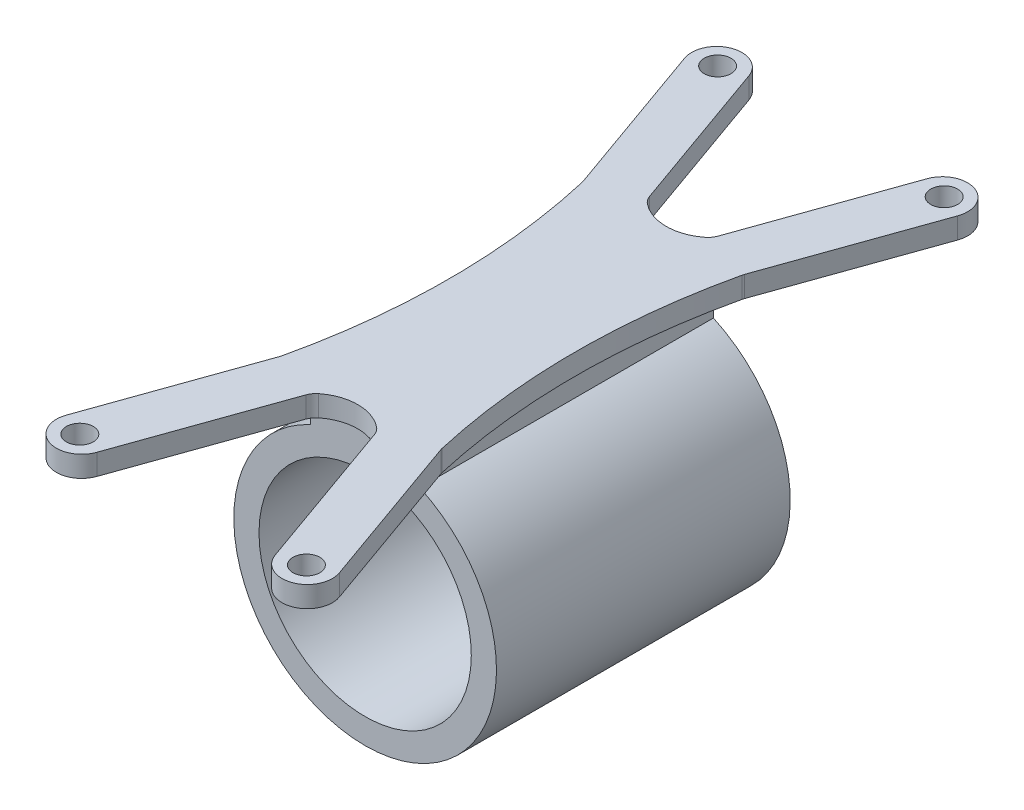
SolidWorks part; units mm, degrees
ref_plane "Front Plane" through (0, 0, 0) normal (0, 0, 1) x (1, 0, 0)
ref_plane "Top Plane" through (0, 0, 0) normal (0, 1, 0) x (1, 0, 0)
ref_plane "Right Plane" through (0, 0, 0) normal (1, 0, 0) x (0, 0, -1)
sketch "Sketch1" plane through (0, 0, 0) normal (0, 0, 1) x (1, 0, 0)
  circle A0 centre (0, 0) radius 12.65
  circle A1 centre (0, 0) radius 15.65
  dimension "D1" = 25.3
  dimension "D2" = 3
extrude "Boss-Extrude1" add sketch "Sketch1" along normal mid plane 35
ref_plane "Plane1" through (0, -35, 0) normal (0, 1, 0) x (1, 0, 0)
ref_plane "Plane3" through (0, 20, 0) normal (0, 1, 0) x (1, 0, 0)
sketch "Sketch4" plane through (0, 20, 0) normal (0, 1, 0) x (1, 0, 0)
  line L0 (-13.5, 0) -> (13.5, 0) construction
  line L1 (-13.5, -38) -> (-13.5, 38) construction
  line L2 (13.5, -38) -> (13.5, 38) construction
  line L4 (-10, -12.5) -> (10, -12.5)
  line L5 (-10, -12.5) -> (-10, 12.5)
  line L6 (-10, 12.5) -> (10, 12.5)
  line L7 (10, -12.5) -> (10, 12.5)
  line L8 (-10, -12.5) -> (10, 12.5) construction
  line L9 (-10, 12.5) -> (10, -12.5) construction
  circle A0 centre (-13.5, 38) radius 1.6
  circle A1 centre (13.5, 38) radius 1.6
  circle A2 centre (-13.5, -38) radius 1.6
  circle A3 centre (13.5, -38) radius 1.6
  point P4 (0, 0)
  point P8 (-13.5, 0)
  point P11 (13.5, 0)
  point P12 (13.5, 0)
  point P16 (0, 0)
  dimension "D3" = 3.2
  dimension "D1" = 27
  dimension "D2" = 76
  dimension "D4" = 20
  dimension "D5" = 25
sketch "Sketch5" plane through (0, 20, 0) normal (0, 1, 0) x (1, 0, 0)
  line L0 (-13.5, -38) -> (0, 0) construction
  line L1 (0, 0) -> (13.5, -38) construction
  line L2 (0, 0) -> (-13.5, 38) construction
  line L3 (0, 0) -> (13.5, 38) construction
  line L4 (-9.5769, 17.9957) -> (-3.9231, 20.0043) construction
  line L5 (-3.9231, 20.0043) -> (-10.6184, 38.8503)
  line L6 (-9.5769, 17.9957) -> (-16.2722, 36.8417)
  line L7 (0, 0) -> (0, 17.9957) construction
  line L8 (3.9231, 20.0043) -> (10.6184, 38.8503)
  line L9 (9.5769, 17.9957) -> (16.2722, 36.8417)
  line L10 (0, 0) -> (19.5583, 0) construction
  line L11 (9.5769, -17.9957) -> (16.2722, -36.8417)
  line L12 (3.9231, -20.0043) -> (10.6184, -38.8503)
  line L13 (-3.9231, -20.0043) -> (-10.6184, -38.8503)
  line L14 (-9.5769, -17.9957) -> (-16.2722, -36.8417)
  line L15 (-3.9231, 20.0043) -> (0, 8.9615)
  line L16 (0, 8.9615) -> (3.9231, 20.0043)
  line L17 (-9.5769, 17.9957) -> (-3.1837, 0)
  line L18 (-13.5, 0) -> (13.5, 0) construction
  line L19 (-3.1837, 0) -> (-9.5769, -17.9957)
  line L20 (9.5769, 17.9957) -> (3.1837, 0)
  line L21 (9.5769, -17.9957) -> (3.1837, 0)
  line L22 (0, 0) -> (0, -29.3249) construction
  line L23 (-3.9231, -20.0043) -> (0, -8.9615)
  line L24 (0, -8.9615) -> (3.9231, -20.0043)
  circle A0 centre (13.5, -38) radius 1.6 construction
  circle A1 centre (-13.5, -38) radius 1.6 construction
  circle A2 centre (13.5, 38) radius 1.6 construction
  circle A3 centre (-13.5, 38) radius 1.6 construction
  circle A4 centre (13.5, -38) radius 1.6
  circle A5 centre (-13.5, -38) radius 1.6
  circle A6 centre (13.5, 38) radius 1.6
  circle A7 centre (-13.5, 38) radius 1.6
  arc A8 (-16.2722, 36.8417) -> (-10.6184, 38.8503) centre (-13.4453, 37.846) cw
  arc A9 (16.2722, 36.8417) -> (10.6184, 38.8503) centre (13.4453, 37.846) ccw
  arc A10 (16.2722, -36.8417) -> (10.6184, -38.8503) centre (13.4453, -37.846) cw
  arc A11 (-16.2722, -36.8417) -> (-10.6184, -38.8503) centre (-13.4453, -37.846) ccw
  arc A12 (-9.5769, 17.9957) -> (-9.5769, -17.9957) centre (-87.5266, 0) cw
  arc A13 (9.5769, 17.9957) -> (9.5769, -17.9957) centre (87.5266, 0) ccw
  arc A14 (-3.9231, -20.0043) -> (3.9231, -20.0043) centre (0, -23.9301) cw
  arc A15 (-3.9231, 20.0043) -> (3.9231, 20.0043) centre (0, 23.9301) ccw
  point P17 (-6.75, 19)
  dimension "D3" = 80
  dimension "D4" = 5.55
  dimension "D1" = 6
  dimension "D2" = 20
extrude "Boss-Extrude4" add sketch "Sketch5" against normal blind 2.5 separate body contours L14 A11 L13 L23 L24 L12 A10 L11 L21 L20 L9 A9 L8 L16 L15 L5 A8 L6 L17 L19 A4 A5 A6 A7 | L17 A12 L19 | A13 L20 L21 | L23 A14 L24 | A15 L15 L16
fillet "Fillet1" radius 2 8 edges at (3.9231, 18.75, 20.0043) (9.5769, 18.75, 17.9957) (-3.9231, 18.75, 20.0043) (-9.5769, 18.75, 17.9957) (-9.5769, 18.75, -17.9957) (9.5769, 18.75, -17.9957) (3.9231, 18.75, -20.0043) (-3.9231, 18.75, -20.0043)
sketch "Sketch6" plane through (0, 17.5, 0) normal (0, -1, 0) x (1, 0, 0)
  line L0 (15.65, 17.5) -> (-15.65, 17.5) construction
  line L1 (6.5, 17.5) -> (-6.5, 17.5)
  line L2 (6.5, 17.5) -> (6.5, -17.5)
  line L3 (6.5, -17.5) -> (-6.5, -17.5)
  line L4 (-6.5, 17.5) -> (-6.5, -17.5)
  line L5 (6.5, 17.5) -> (-6.5, -17.5) construction
  line L6 (6.5, -17.5) -> (-6.5, 17.5) construction
  point P0 (0, 0)
  dimension "D2" = 13
extrude "Boss-Extrude5" add sketch "Sketch6" along normal up to next
sketch "Sketch7" plane through (0, 0, 17.5) normal (0, 0, 1) x (1, 0, 0)
  circle A0 centre (0, 0) radius 12.65 construction
  circle A1 centre (0, 0) radius 12.65
